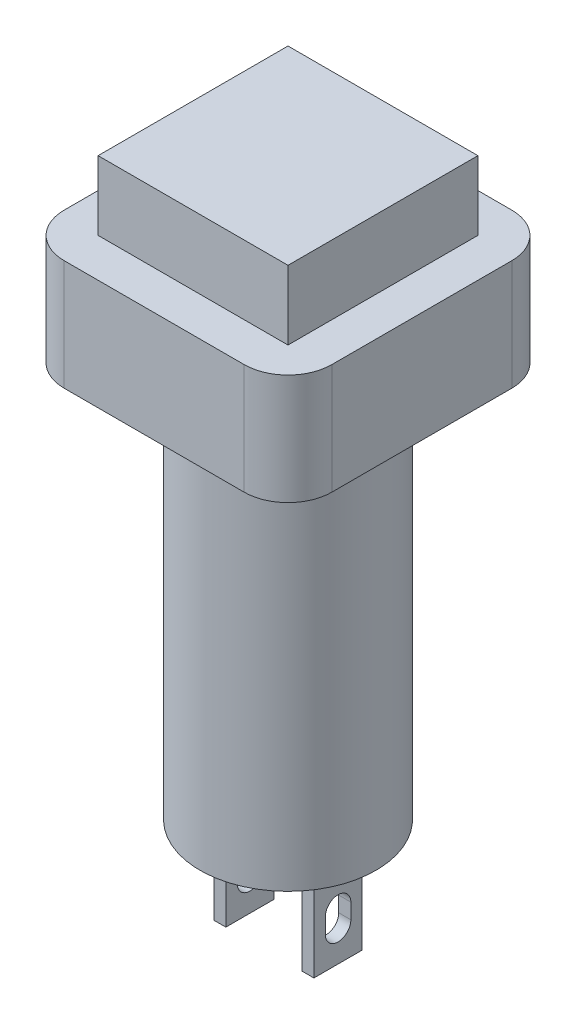
SolidWorks part; units mm, degrees
ref_plane "Front Plane" through (0, 0, 0) normal (0, 0, 1) x (1, 0, 0)
ref_plane "Top Plane" through (0, 0, 0) normal (0, 1, 0) x (1, 0, 0)
ref_plane "Right Plane" through (0, 0, 0) normal (1, 0, 0) x (0, 0, -1)
sketch "Sketch1" plane through (0, 0, 0) normal (0, 1, 0) x (1, 0, 0)
  line L1 (0, 0) -> (15.5, 0)
  line L2 (0, 0) -> (0, 15.5)
  line L3 (0, 15.5) -> (15.5, 15.5)
  line L4 (15.5, 0) -> (15.5, 15.5)
  dimension "D1" = 15.5
  dimension "D2" = 15.5
extrude "Boss-Extrude1" add sketch "Sketch1" along normal blind 6.4
fillet "Fillet1" radius 2.54 1 edges at (15.5, 3.2, 0)
fillet "Fillet2" radius 2.54 1 edges at (0, 3.2, 0)
fillet "Fillet3" radius 2.54 1 edges at (15.5, 3.2, -15.5)
fillet "Fillet4" radius 2.54 1 edges at (0, 3.2, -15.5)
sketch "Sketch2" plane through (0, 6.4, 0) normal (0, 1, 0) x (1, 0, 0)
  line L0 (2.54, 0) -> (12.96, 0) construction
  line L1 (2.25, 13.25) -> (13.25, 13.25)
  line L2 (2.25, 13.25) -> (2.25, 2.25)
  line L3 (2.25, 2.25) -> (13.25, 2.25)
  line L4 (13.25, 13.25) -> (13.25, 2.25)
  line L5 (0, 12.96) -> (0, 2.54) construction
  point P6 (7.75, 2.25)
  point P7 (7.75, 0)
  point P10 (0, 7.75)
  point P11 (2.25, 7.75)
  dimension "D1" = 11
  dimension "D2" = 11
extrude "Boss-Extrude2" add sketch "Sketch2" along normal blind 4
sketch "Sketch3" plane through (0, 0, 0) normal (0, -1, 0) x (1, 0, 0)
  line L0 (2.54, 0) -> (12.96, 0) construction
  line L1 (15.5, -2.54) -> (15.5, -12.96) construction
  circle A0 centre (7.75, -7.75) radius 5.1
  point P4 (7.75, 0)
  point P7 (15.5, -7.75)
  dimension "D1" = 10.2
extrude "Boss-Extrude3" add sketch "Sketch3" along normal blind 22.9
sketch "Sketch4" plane through (0, -22.9, 0) normal (0, -1, 0) x (1, 0, 0)
  line L0 (7.75, -10.367) -> (7.75, -4.9695) construction
  line L1 (4.85, -6.35) -> (5.55, -6.35)
  line L2 (4.85, -6.35) -> (4.85, -9.15)
  line L3 (4.85, -9.15) -> (5.55, -9.15)
  line L4 (5.55, -6.35) -> (5.55, -9.15)
  line L5 (9.95, -6.35) -> (10.65, -6.35)
  line L6 (9.95, -6.35) -> (9.95, -9.15)
  line L7 (9.95, -9.15) -> (10.65, -9.15)
  line L8 (10.65, -6.35) -> (10.65, -9.15)
  line L9 (2.54, 0) -> (12.96, 0) construction
  line L10 (6.6256, -7.75) -> (8.5605, -7.75) construction
  line L11 (15.5, -2.54) -> (15.5, -12.96) construction
  point P12 (7.75, 0)
  point P17 (15.5, -7.75)
  point P18 (5.55, -7.75)
  point P19 (9.95, -7.75)
  dimension "D1" = 2.8
  dimension "D2" = 0.7
  dimension "D3" = 0.7
  dimension "D4" = 2.8
  dimension "D5" = 5.8
  dimension "D6" = 2.9
extrude "Boss-Extrude4" add sketch "Sketch4" along normal blind 5.8
sketch "Sketch5" plane through (10.65, 0, 0) normal (1, 0, 0) x (0, 0, -1)
  line L0 (7.75, -25.963) -> (7.75, -26.8485) construction
  line L1 (8.4892, -25.963) -> (8.4892, -26.8485)
  line L2 (7.0108, -25.963) -> (7.0108, -26.8485)
  line L3 (9.15, -28.7) -> (6.35, -28.7) construction
  arc A0 (8.4892, -25.963) -> (7.0108, -25.963) centre (7.75, -25.963) ccw
  arc A1 (7.0108, -26.8485) -> (8.4892, -26.8485) centre (7.75, -26.8485) ccw
  point P2 (7.75, -26.4057)
  point P9 (7.75, -28.7)
extrude "Cut-Extrude1" cut sketch "Sketch5" against normal through all
